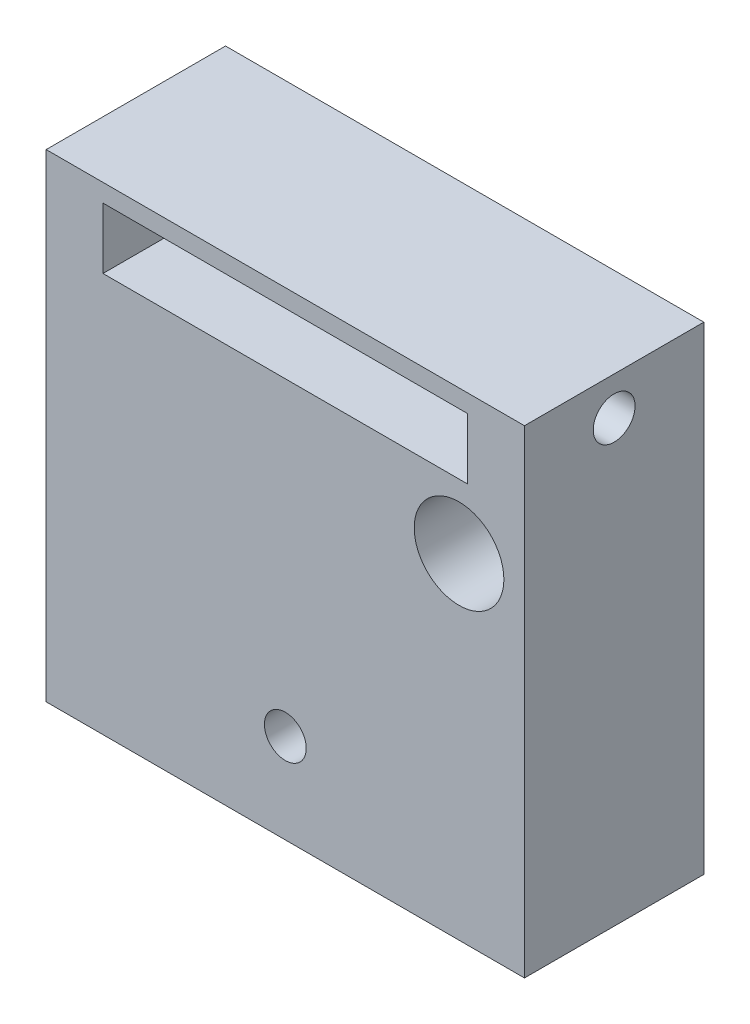
SolidWorks part; units mm, degrees
material "Balsa"
ref_plane "Plan de face" through (0, 0, 0) normal (0, 0, 1) x (1, 0, 0)
ref_plane "Plan de dessus" through (0, 0, 0) normal (0, 1, 0) x (1, 0, 0)
ref_plane "Plan de droite" through (0, 0, 0) normal (1, 0, 0) x (0, 0, -1)
sketch "Sketch1" plane through (0, 0, 0) normal (0, 0, 1) x (1, 0, 0)
  line L1 (-40, -40) -> (40, -40)
  line L2 (-40, -40) -> (-40, 40)
  line L3 (-40, 40) -> (40, 40)
  line L4 (40, -40) -> (40, 40)
  line L5 (-40, -40) -> (40, 40) construction
  line L6 (-40, 40) -> (40, -40) construction
  point P0 (0, 0)
  dimension "D1" = 80
  dimension "D2" = 80
extrude "Boss-Extrude1" add sketch "Sketch1" along normal blind 30
sketch "Sketch2" plane through (0, 0, 30) normal (0, 0, 1) x (1, 0, 0)
  line L0 (40, 40) -> (-40, 40) construction
  line L1 (-30.5, 26.8) -> (30.5, 26.8)
  line L2 (-30.5, 26.8) -> (-30.5, 37)
  line L3 (-30.5, 37) -> (30.5, 37)
  line L4 (30.5, 26.8) -> (30.5, 37)
  line L5 (-30.5, 26.8) -> (30.5, 37) construction
  line L6 (-30.5, 37) -> (30.5, 26.8) construction
  line L7 (-40, 40) -> (-40, -40) construction
  point P0 (0, 31.9)
  dimension "D1" = 61
  dimension "D2" = 10.2
  dimension "D3" = 3
  dimension "D4" = 9.5
extrude "Cut-Extrude1" cut sketch "Sketch2" against normal through all
sketch "Sketch3" plane through (0, 0, 0) normal (0, 0, -1) x (-1, 0, 0)
  line L0 (40, -40) -> (-40, -40) construction
  line L1 (-20, -40) -> (20, -40)
  line L2 (-20, -40) -> (-20, -15)
  line L3 (-20, -15) -> (20, -15)
  line L4 (20, -40) -> (20, -15)
  line L5 (-40, -40) -> (-40, 40) construction
  line L6 (40, 40) -> (40, -40) construction
  dimension "D1" = 20
  dimension "D2" = 20
  dimension "D3" = 25
extrude "Cut-Extrude2" cut sketch "Sketch3" against normal blind 20
sketch "Sketch4" plane through (0, 0, 20) normal (0, 0, -1) x (-1, 0, 0)
  line L0 (-40, -40) -> (-40, 40) construction
  line L1 (40, -40) -> (-40, -40) construction
  circle A0 centre (0, -25) radius 3.5
  dimension "D1" = 7
  dimension "D2" = 40
  dimension "D3" = 15
extrude "Cut-Extrude3" cut sketch "Sketch4" against normal through all
sketch "Sketch5" plane through (40, 0, 0) normal (1, 0, 0) x (0, 0, -1)
  line L0 (-30, -40) -> (-30, 40) construction
  circle A0 centre (-15, 33.619) radius 3.5
  dimension "D2" = 7
  dimension "D1" = 15
extrude "Cut-Extrude4" cut sketch "Sketch5" against normal through all
sketch "Sketch6" plane through (0, 0, 30) normal (0, 0, 1) x (1, 0, 0)
  line L0 (-40, -40) -> (40, -40) construction
  circle A0 centre (29.0563, 16) radius 7.5
  dimension "D1" = 15
  dimension "D2" = 56
extrude "Cut-Extrude5" cut sketch "Sketch6" against normal through all
